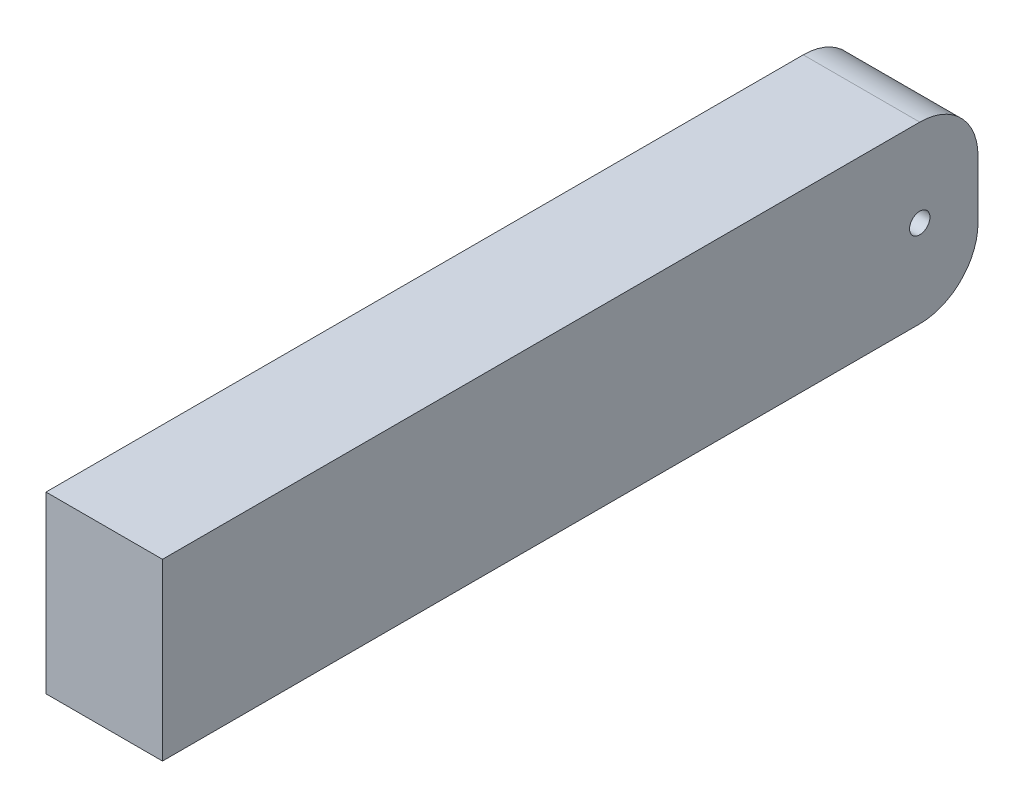
SolidWorks part; units mm, degrees
ref_plane "Front Plane" through (0, 0, 0) normal (0, 0, 1) x (1, 0, 0)
ref_plane "Top Plane" through (0, 0, 0) normal (0, 1, 0) x (1, 0, 0)
ref_plane "Right Plane" through (0, 0, 0) normal (1, 0, 0) x (0, 0, -1)
sketch "Sketch1" plane through (0, 0, 0) normal (0, 0, 1) x (1, 0, 0)
  line L1 (-10, 15) -> (10, 15)
  line L2 (-10, 15) -> (-10, -15)
  line L3 (-10, -15) -> (10, -15)
  line L4 (10, 15) -> (10, -15)
  line L5 (-10, 15) -> (10, -15) construction
  line L6 (-10, -15) -> (10, 15) construction
  point P0 (0, 0)
  dimension "D1" = 30
  dimension "D2" = 20
extrude "Boss-Extrude1" add sketch "Sketch1" along normal blind 140
fillet "Fillet1" radius 10 2 edges at (0, -15, 0) (0, 15, 0)
sketch "Sketch2" plane through (10, 0, 0) normal (1, 0, 0) x (0, 0, -1)
  line L0 (0, 0) -> (-10, 0) construction
  circle A0 centre (-10, 0) radius 1.75
  dimension "D1" = 3.5
  dimension "D2" = 10
extrude "Cut-Extrude1" cut sketch "Sketch2" against normal through all
sketch "Sketch3" plane through (-10, 0, 0) normal (-1, 0, 0) x (0, 0, 1)
  circle A2 centre (10, 0) radius 4.75
  circle A3 centre (10, 0) radius 4.75
  dimension "D1" = 3
extrude "Cut-Extrude2" cut sketch "Sketch3" against normal blind 15
